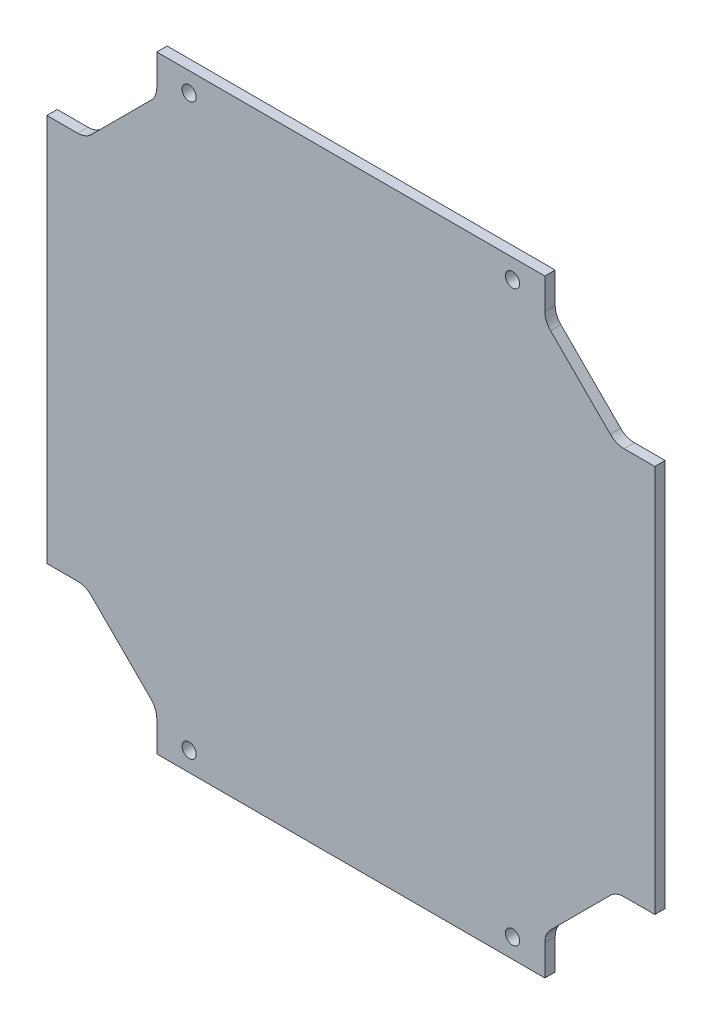
SolidWorks part; units mm, degrees
ref_plane "Front Plane" through (0, 0, 0) normal (0, 0, 1) x (1, 0, 0)
ref_plane "Top Plane" through (0, 0, 0) normal (0, 1, 0) x (1, 0, 0)
ref_plane "Right Plane" through (0, 0, 0) normal (1, 0, 0) x (0, 0, -1)
sketch "Sketch2" plane through (0, 0, 0) normal (0, 0, 1) x (1, 0, 0)
  line L0 (-86.5653, 74.9519) -> (-86.5653, 14.9519)
  line L1 (-69.5653, -2.0481) -> (-9.5653, -2.0481)
  line L2 (7.4347, 74.9519) -> (7.4347, 14.9519)
  line L3 (-69.5653, 91.9519) -> (-9.5653, 91.9519)
  line L4 (-86.5653, 14.9519) -> (-80.5653, 14.9519)
  line L7 (-69.5653, 3.9519) -> (-69.5653, -2.0481)
  line L8 (-86.5653, 74.9519) -> (-80.5653, 74.9519)
  line L11 (-69.5653, 85.9519) -> (-69.5653, 91.9519)
  line L12 (-9.5653, 91.9519) -> (-9.5653, 85.9519)
  line L15 (1.4347, 74.9519) -> (7.4347, 74.9519)
  line L16 (7.4347, 14.9519) -> (1.4347, 14.9519)
  line L19 (-9.5653, 3.9519) -> (-9.5653, -2.0481)
  line L20 (-80.5653, 74.9519) -> (-69.5653, 85.9519)
  line L21 (-9.5653, 85.9519) -> (1.4347, 74.9519)
  line L22 (-9.5653, 3.9519) -> (1.4347, 14.9519)
  line L23 (-80.5653, 14.9519) -> (-69.5653, 3.9519)
  circle A12 centre (-64.5653, 88.9519) radius 1.1
  circle A13 centre (-64.5653, 0.9519) radius 1.1
  circle A14 centre (-14.5653, 88.9519) radius 1.1
  circle A15 centre (-14.5653, 0.9519) radius 1.1
  dimension "D1" = 94
  dimension "D6" = 2.2
  dimension "D11" = 60
  dimension "D5" = 17
  dimension "D4" = 6
  dimension "D2" = 94
  dimension "D3" = 3
  dimension "D7" = 22
  dimension "D8" = 22
  dimension "D9" = 3
  dimension "D10" = 60
  dimension "D12" = 135
extrude "Boss-Extrude1" add sketch "Sketch2" along normal blind 1.6
fillet "Fillet2" radius 3 8 edges at (-80.5653, 14.9519, 0.8) (-69.5653, 3.9519, 0.8) (-9.5653, 3.9519, 0.8) (1.4347, 14.9519, 0.8) (-9.5653, 85.9519, 0.8) (1.4347, 74.9519, 0.8) (-80.5653, 74.9519, 0.8) (-69.5653, 85.9519, 0.8)
